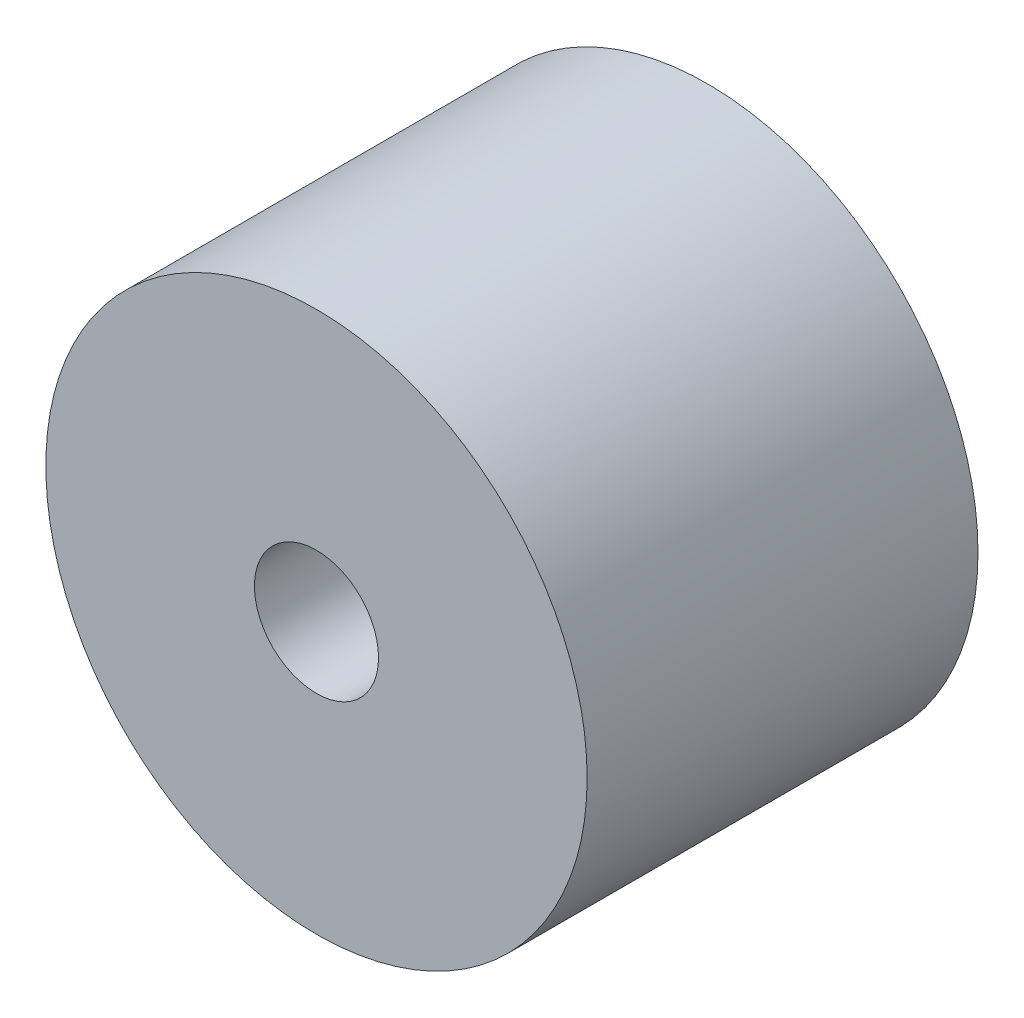
SolidWorks part; units mm, degrees
ref_plane "Front Plane" through (0, 0, 0) normal (0, 0, 1) x (1, 0, 0)
ref_plane "Top Plane" through (0, 0, 0) normal (0, 1, 0) x (1, 0, 0)
ref_plane "Right Plane" through (0, 0, 0) normal (1, 0, 0) x (0, 0, -1)
sketch "Sketch1" plane through (0, 0, 0) normal (0, 0, 1) x (1, 0, 0)
  circle A0 centre (0, 0) radius 27.7
  dimension "D1" = 55.4
extrude "Boss-Extrude1" add sketch "Sketch1" along normal blind 40
sketch "Sketch2" plane through (0, 0, 40) normal (0, 0, 1) x (1, 0, 0)
  circle A0 centre (0, 0) radius 6.35
  dimension "D1" = 12.7
extrude "Cut-Extrude1" cut sketch "Sketch2" against normal blind 40
